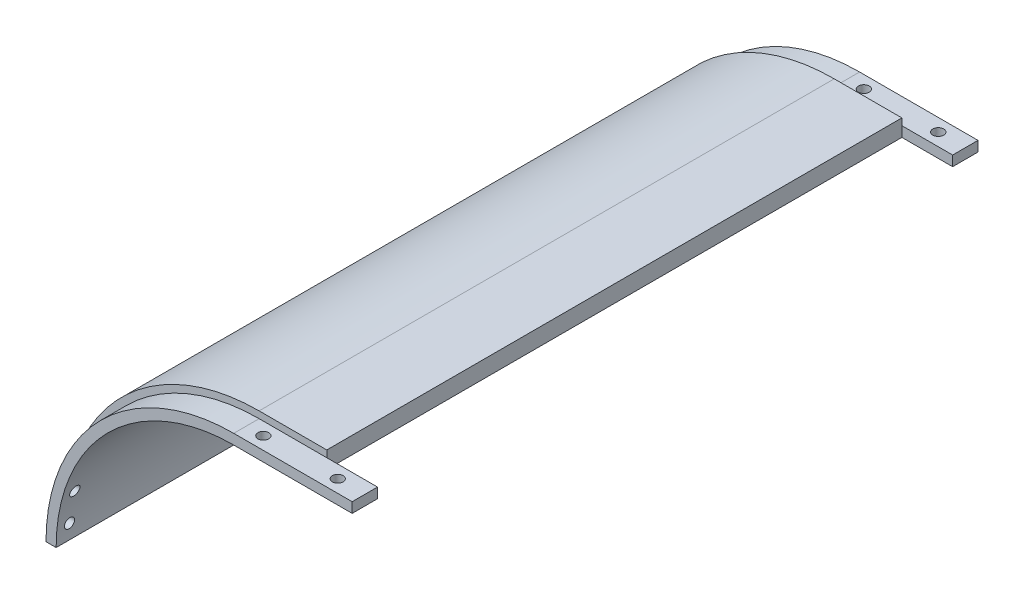
SolidWorks part; units mm, degrees
ref_plane "Front Plane" through (0, 0, 0) normal (0, 0, 1) x (1, 0, 0)
ref_plane "Top Plane" through (0, 0, 0) normal (0, 1, 0) x (1, 0, 0)
ref_plane "Right Plane" through (0, 0, 0) normal (1, 0, 0) x (0, 0, -1)
sketch "Sketch1" plane through (0, 0, 0) normal (0, 0, 1) x (1, 0, 0)
  line L2 (-60, -57.5) -> (60, -57.5) construction
  line L3 (60, 57.5) -> (-60, 57.5)
  line L4 (-60, -52.5) -> (60, -52.5) construction
  line L5 (60, 52.5) -> (-60, 52.5)
  line L10 (57.05, 52.5) -> (52.95, 52.5)
  line L11 (35.05, 52.5) -> (30.95, 52.5)
  line L12 (13.05, 52.5) -> (8.95, 52.5)
  line L13 (-8.95, 52.5) -> (-13.05, 52.5)
  line L14 (-52.95, 52.5) -> (-57.05, 52.5)
  line L15 (-30.95, 52.5) -> (-35.05, 52.5)
  line L16 (-117.5, 0) -> (-112.5, 0)
  line L17 (-133.4321, 0) -> (-117.5, 0) construction
  line L18 (-112.5, 0) -> (112.5, 0) construction
  line L19 (112.5, 0) -> (117.5, 0)
  line L20 (117.5, 0) -> (142.1657, 0) construction
  arc A2 (-60, 57.5) -> (-117.5, 0) centre (-60, 0) ccw
  arc A3 (117.5, 0) -> (60, 57.5) centre (60, 0) ccw
  arc A4 (-60, 52.5) -> (-112.5, 0) centre (-60, 0) ccw
  arc A5 (112.5, 0) -> (60, 52.5) centre (60, 0) ccw
  arc A6 (-110.1443, 15.55) -> (-111.2362, 11.45) centre (-60, 0) ccw
  arc A7 (-112.0898, 6.55) -> (-112.4428, 2.45) centre (-60, 0) ccw
  arc A10 (112.4428, 2.45) -> (112.0898, 6.55) centre (60, 0) ccw
  arc A11 (111.2362, 11.45) -> (110.1443, 15.55) centre (60, 0) ccw
  arc A12 (60, -57.5) -> (117.5, 0) centre (60, 0) ccw construction
  arc A13 (60, -57.5) -> (60, 57.5) centre (60, 0) ccw construction
  arc A14 (60, -52.5) -> (112.5, 0) centre (60, 0) ccw construction
  arc A15 (60, -52.5) -> (60, 52.5) centre (60, 0) ccw construction
  arc A16 (-112.5, 0) -> (-60, -52.5) centre (-60, 0) ccw construction
  arc A17 (-60, 52.5) -> (-60, -52.5) centre (-60, 0) ccw construction
  arc A18 (-117.5, 0) -> (-60, -57.5) centre (-60, 0) ccw construction
  arc A19 (-60, 57.5) -> (-60, -57.5) centre (-60, 0) ccw construction
  dimension "D1" = 5
extrude "Boss-Extrude1" add sketch "Sketch1" along normal mid plane 185 contours A5 L19 A3 L3 A2 L16 A4 L5 A11
sketch "Sketch2" plane through (0, 0, 0) normal (1, 0, 0) x (0, 0, -1)
  line L0 (-92.5, 57.5) -> (-92.5, 0) construction
  line L1 (-92.5, 0) -> (92.5, 0) construction
  circle A0 centre (-88.75, 4.5) radius 1.5
  circle A1 centre (-88.75, 13.5) radius 1.5
  point P8 (0, 0)
  dimension "D1" = 3
  dimension "D4" = 3
  dimension "D2" = 3.75
  dimension "D3" = 4.5
  dimension "D5" = 9
extrude "Cut-Extrude1" cut sketch "Sketch2" against normal through all both and the other way through all
sketch "Sketch4" plane through (0, 57.5, 0) normal (0, 1, 0) x (1, 0, 0)
  line L0 (0, -180.3175) -> (0, -193.1229) construction
  line L1 (60, -92.5) -> (-60, -92.5) construction
  circle A0 centre (-55, -88.75) radius 1.6
  circle A1 centre (-33, -88.75) radius 1.6
  circle A2 centre (-11, -88.75) radius 1.6
  circle A3 centre (11, -88.75) radius 1.6
  circle A4 centre (33, -88.75) radius 1.6
  circle A5 centre (55, -88.75) radius 1.6
  dimension "D1" = 3.2
  dimension "D2" = 3.75
  dimension "D4" = 11
  dimension "D3" = 6
extrude "Cut-Extrude2" cut sketch "Sketch4" against normal through all both
sketch "Sketch5" plane through (0, 0, -92.5) normal (0, 0, -1) x (-1, 0, 0)
  line L0 (117.5, 0) -> (112.5, 0) construction
  line L1 (-112.5, 0) -> (-117.5, 0) construction
  line L2 (-60, 57.5) -> (60, 57.5) construction
  line L3 (117.5, 0) -> (112.5, 0)
  line L4 (-112.5, 0) -> (-117.5, 0)
  line L5 (-60, 57.5) -> (60, 57.5)
  line L6 (-60, 55.5) -> (60, 55.5)
  arc A0 (-60, 57.5) -> (-117.5, 0) centre (-60, 0) ccw construction
  arc A1 (117.5, 0) -> (60, 57.5) centre (60, 0) ccw construction
  arc A2 (-60, 57.5) -> (-117.5, 0) centre (-60, 0) ccw
  arc A3 (117.5, 0) -> (60, 57.5) centre (60, 0) ccw
  arc A4 (115.5, 0) -> (60, 55.5) centre (60, 0) ccw
  arc A5 (-60, 55.5) -> (-115.5, 0) centre (-60, 0) ccw
  arc M6 (117.5, 0) -> (60, 57.5) centre (60, 0) ccw
  line M7 (60, 57.5) -> (-60, 57.5)
  arc M8 (-60, 57.5) -> (-117.5, 0) centre (-60, 0) ccw
  line M9 (-117.5, 0) -> (-112.5, 0)
  dimension "D1" = 2
extrude "Cut-Extrude3" cut sketch "Sketch5" against normal blind 7.5 contours A5 L6 A4 L3 M6 M7 M8 M9
mirror "Mirror1" about plane through (0, 0, 0) normal (0, 0, 1) of "Cut-Extrude3", "Cut-Extrude1", "Cut-Extrude2"
sketch "Sketch6" plane through (0, 57.5, 0) normal (0, 1, 0) x (1, 0, 0)
  line L1 (-40, 85) -> (-25, 85)
  line L2 (-40, 85) -> (-40, -85)
  line L3 (-40, -85) -> (-25, -85)
  line L4 (40, 85) -> (40, -85)
  line L5 (-40, 85) -> (40, -85) construction
  line L6 (-40, -85) -> (40, 85) construction
  line L7 (60, -85) -> (-60, -85) construction
  line L8 (25, 85) -> (25, 92.5)
  line L9 (60, 92.5) -> (-60, 92.5) construction
  line L10 (-25, 85) -> (-25, 92.5)
  line L11 (-179.3814, 0) -> (208.5632, 0) construction
  line L12 (-25, -85) -> (-25, -92.5)
  line L13 (25, -85) -> (25, -92.5)
  line L14 (25, -92.5) -> (-25, -92.5)
  line L15 (-25, 92.5) -> (25, 92.5)
  line L16 (-25, 85) -> (25, 85) construction
  line L17 (25, 85) -> (40, 85)
  line L18 (-25, -85) -> (25, -85) construction
  line L19 (25, -85) -> (40, -85)
  point P0 (0, 0)
  dimension "D1" = 170
  dimension "D2" = 80
  dimension "D3" = 25
  dimension "D4" = 50
extrude "Cut-Extrude5" cut sketch "Sketch6" against normal blind 7.5
